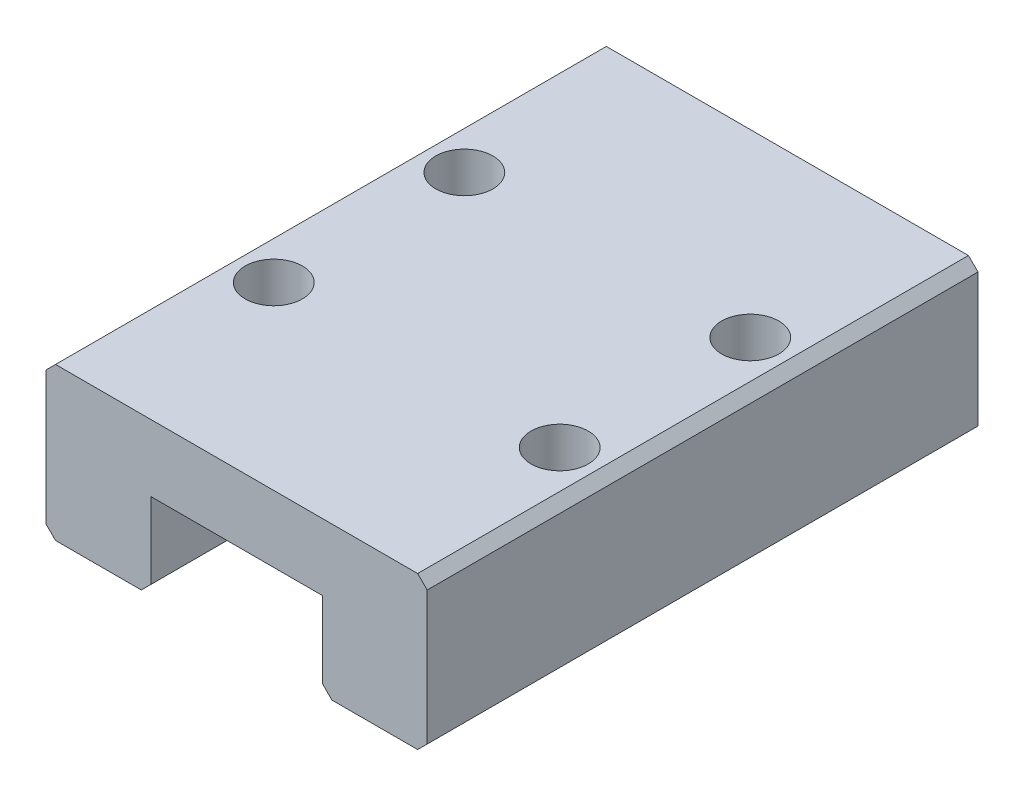
SolidWorks part; units mm, degrees
ref_plane "前视基准面" through (0, 0, 0) normal (0, 0, 1) x (1, 0, 0)
ref_plane "上视基准面" through (0, 0, 0) normal (0, 1, 0) x (1, 0, 0)
ref_plane "右视基准面" through (0, 0, 0) normal (1, 0, 0) x (0, 0, -1)
sketch "草图1" plane through (0, 0, 0) normal (0, 0, 1) x (1, 0, 0)
  line L0 (-4.5, 0) -> (-4.5, -4.5)
  line L1 (-4.5, -4.5) -> (-10, -4.5)
  line L2 (-10, -4.5) -> (-10, 3.5)
  line L3 (-10, 3.5) -> (10, 3.5)
  line L4 (0, 3.5) -> (0, 0) construction
  line L5 (4.5, 0) -> (-4.5, 0)
  line L6 (10, -4.5) -> (10, 3.5)
  line L7 (4.5, -4.5) -> (10, -4.5)
  line L8 (4.5, 0) -> (4.5, -4.5)
  dimension "D1" = 10
  dimension "D2" = 8
  dimension "D3" = 3.5
  dimension "D4" = 5.5
extrude "凸台-拉伸1" add sketch "草图1" along normal mid plane 28.9
sketch "草图2" plane through (0, 3.5, 0) normal (0, 1, 0) x (1, 0, 0)
  line L1 (7.5, -5) -> (-7.5, -5) construction
  line L2 (7.5, -5) -> (7.5, 5) construction
  line L3 (7.5, 5) -> (-7.5, 5) construction
  line L4 (-7.5, -5) -> (-7.5, 5) construction
  line L5 (7.5, -5) -> (-7.5, 5) construction
  line L6 (7.5, 5) -> (-7.5, -5) construction
  circle A0 centre (-7.5, 5) radius 1.5
  circle A1 centre (7.5, 5) radius 1.5
  circle A2 centre (-7.5, -5) radius 1.5
  circle A3 centre (7.5, -5) radius 1.5
  point P0 (0, 0)
  dimension "D3" = 3
  dimension "D1" = 10
  dimension "D2" = 15
extrude "切除-拉伸1" cut sketch "草图2" against normal blind 3
chamfer "倒角1" distance 0.5 angle 45 6 edges at (4.5, -4.5, 0) (-4.5, -4.5, 0) (10, -4.5, 0) (-10, -4.5, 0) (10, 3.5, 0) (-10, 3.5, 0)
